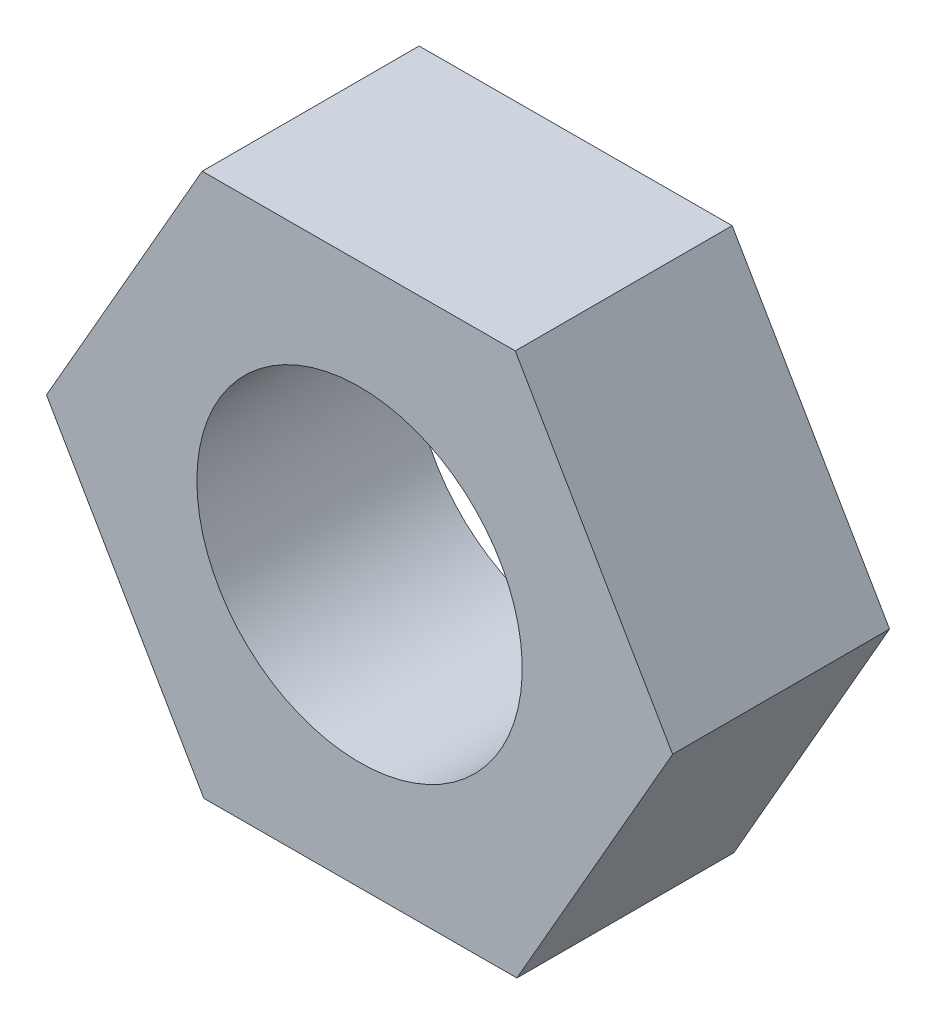
SolidWorks part; units mm, degrees
ref_plane "Front Plane" through (0, 0, 0) normal (0, 0, 1) x (1, 0, 0)
ref_plane "Top Plane" through (0, 0, 0) normal (0, 1, 0) x (1, 0, 0)
ref_plane "Right Plane" through (0, 0, 0) normal (1, 0, 0) x (0, 0, -1)
sketch "Sketch1" plane through (0, 0, 0) normal (0, 0, 1) x (1, 0, 0)
  line L1 (4.6067, -7.9236) -> (9.1654, 0.0278)
  line L2 (9.1654, 0.0278) -> (4.5587, 7.9513)
  line L3 (4.5587, 7.9513) -> (-4.6067, 7.9236)
  line L4 (-4.6067, 7.9236) -> (-9.1654, -0.0278)
  line L5 (-9.1654, -0.0278) -> (-4.5587, -7.9513)
  line L6 (-4.5587, -7.9513) -> (4.6067, -7.9236)
  circle A0 centre (0, 0) radius 7.9375 construction
  dimension "D1" = 15.875
extrude "Boss-Extrude1" add sketch "Sketch1" along normal blind 6.35
sketch "Sketch2" plane through (0, 0, 0) normal (0, 0, -1) x (-1, 0, 0)
  circle A0 centre (0, 0) radius 4.7625
  dimension "D1" = 9.525
extrude "Cut-Extrude1" cut sketch "Sketch2" against normal through all
